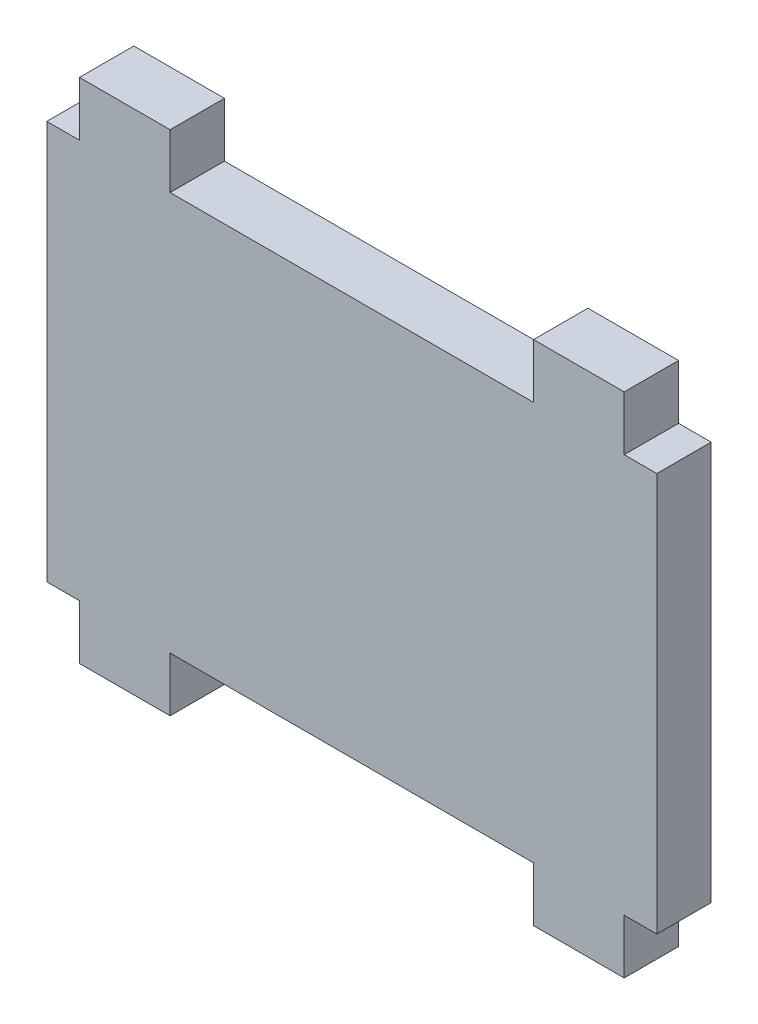
SolidWorks part; units mm, degrees
material "Balsa"
ref_plane "Alzado" through (0, 0, 0) normal (0, 0, 1) x (1, 0, 0)
ref_plane "Planta" through (0, 0, 0) normal (0, 1, 0) x (1, 0, 0)
ref_plane "Vista lateral" through (0, 0, 0) normal (1, 0, 0) x (0, 0, -1)
sketch "Croquis3" plane through (0, 0, 0) normal (0, 0, 1) x (1, 0, 0)
  line L0 (25.05, 0) -> (26.85, 0)
  line L1 (0, 0) -> (1.8, 0)
  line L2 (0, 0) -> (0, 22)
  line L3 (0, 22) -> (1.8, 22)
  line L4 (33.65, 0) -> (33.65, 22)
  line L8 (25.05, 0) -> (25.05, 10)
  line L9 (8.6, 10) -> (8.6, 0)
  line L10 (6.8, 0) -> (8.6, 0)
  line L12 (1.8, 0) -> (1.8, -3)
  line L13 (1.8, -3) -> (6.8, -3)
  line L14 (6.8, 0) -> (6.8, -3)
  line L16 (26.85, 0) -> (26.85, -3)
  line L17 (26.85, -3) -> (31.85, -3)
  line L18 (31.85, 0) -> (31.85, -3)
  line L19 (31.85, 0) -> (33.65, 0)
  line L21 (1.8, 22) -> (1.8, 25)
  line L22 (1.8, 25) -> (6.8, 25)
  line L23 (6.8, 22) -> (6.8, 25)
  line L25 (26.85, 22) -> (26.85, 25)
  line L26 (26.85, 25) -> (31.85, 25)
  line L27 (31.85, 22) -> (31.85, 25)
  line L28 (6.8, 22) -> (26.85, 22)
  line L29 (31.85, 22) -> (33.65, 22)
  line L30 (8.6, 0) -> (25.05, 0)
  dimension "D1" = 33.65
  dimension "D2" = 22
  dimension "D3" = 5
  dimension "D4" = 1.8
  dimension "D5" = 3
  dimension "D6" = 3
  dimension "D7" = 5
  dimension "D8" = 1.8
  dimension "D10" = 5
  dimension "D11" = 5
  dimension "D12" = 3
  dimension "D13" = 3
  dimension "D14" = 1.8
  dimension "D15" = 1.8
extrude "Saliente-Extruir1" add sketch "Croquis3" along normal blind 3
